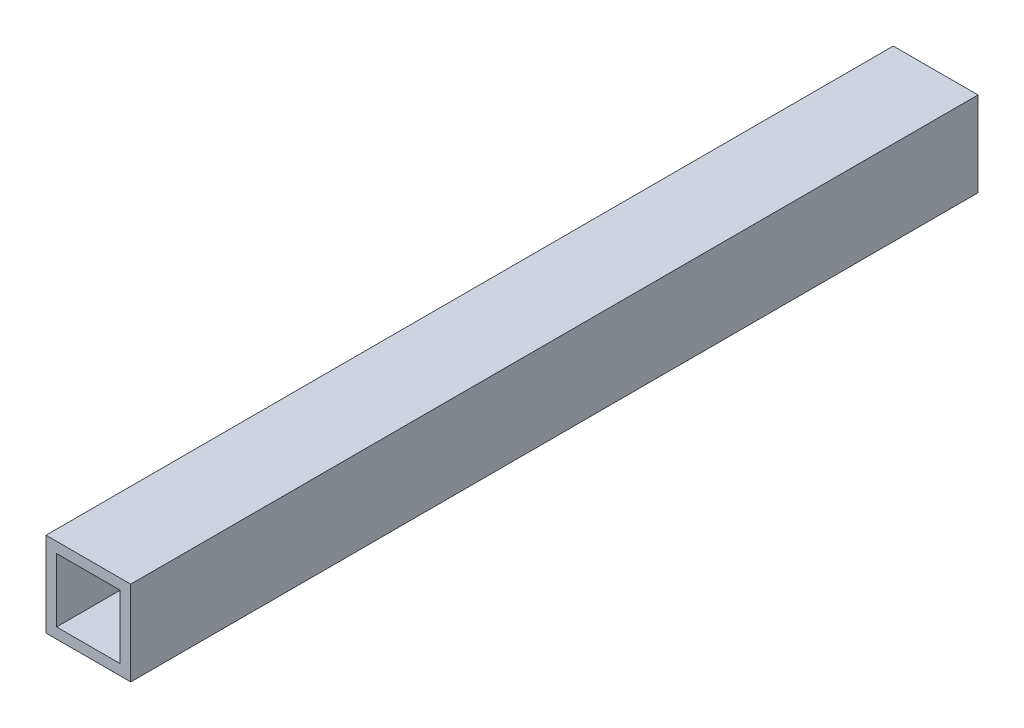
SolidWorks part; units mm, degrees
ref_plane "Front Plane" through (0, 0, 0) normal (0, 0, 1) x (1, 0, 0)
ref_plane "Top Plane" through (0, 0, 0) normal (0, 1, 0) x (1, 0, 0)
ref_plane "Right Plane" through (0, 0, 0) normal (1, 0, 0) x (0, 0, -1)
sketch "Sketch1" plane through (0, 0, 0) normal (0, 0, 1) x (1, 0, 0)
  line L1 (0, 0) -> (-25.4, 0)
  line L2 (0, 0) -> (0, 25.4)
  line L3 (0, 25.4) -> (-25.4, 25.4)
  line L4 (-25.4, 0) -> (-25.4, 25.4)
  line L5 (-3.175, 3.175) -> (-22.225, 3.175)
  line L6 (-3.175, 3.175) -> (-3.175, 22.225)
  line L7 (-3.175, 22.225) -> (-22.225, 22.225)
  line L8 (-22.225, 3.175) -> (-22.225, 22.225)
  dimension "D1" = 25.4
  dimension "D2" = 25.4
  dimension "D3" = 3.175
  dimension "D4" = 3.175
  dimension "D5" = 3.175
  dimension "D6" = 3.175
extrude "Boss-Extrude1" add sketch "Sketch1" along normal blind 254
